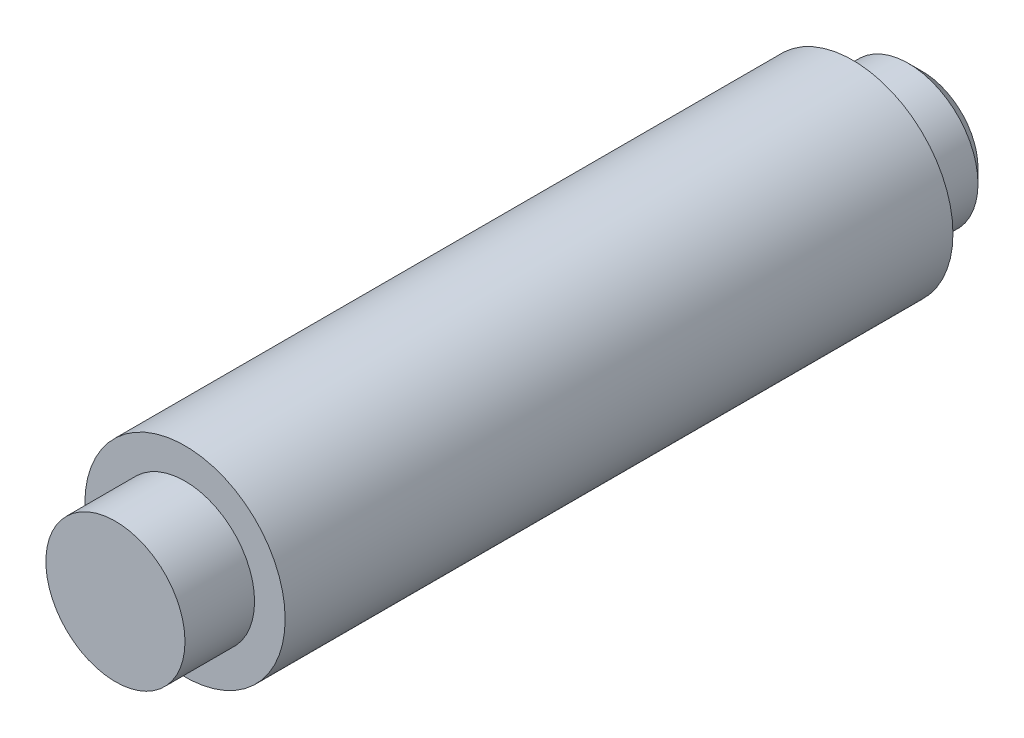
SolidWorks part; units mm, degrees
ref_plane "Front Plane" through (0, 0, 0) normal (0, 0, 1) x (1, 0, 0)
ref_plane "Top Plane" through (0, 0, 0) normal (0, 1, 0) x (1, 0, 0)
ref_plane "Right Plane" through (0, 0, 0) normal (1, 0, 0) x (0, 0, -1)
sketch "Sketch2" plane through (0, 0, 0) normal (0, 0, 1) x (1, 0, 0)
  circle A0 centre (0, 0) radius 1.25
  dimension "D1" = 2.5
sketch "Sketch3" plane through (0, 0, 0) normal (0, 0, 1) x (1, 0, 0)
  line L5 (-3.6, 3.6) -> (3.6, 3.6) construction
  line L6 (-3.6, 3.6) -> (-3.6, -3.6) construction
  line L7 (-3.6, -3.6) -> (3.6, -3.6) construction
  line L8 (3.6, 3.6) -> (3.6, -3.6) construction
  circle A0 centre (0, 0) radius 3.6
  point P4 (0, 3.6)
  point P6 (-3.6, 0)
  dimension "D1" = 7.2
extrude "Boss-Extrude1" add sketch "Sketch3" along normal blind 24
sketch "Sketch4" plane through (0, 0, 0) normal (0, 0, 1) x (1, 0, 0)
  circle A0 centre (0, 0) radius 2.5
  dimension "D1" = 5
extrude "Boss-Extrude2" add sketch "Sketch4" against normal blind 2.5
sketch "Sketch5" plane through (0, 0, 24) normal (0, 0, 1) x (1, 0, 0)
  circle A0 centre (0, 0) radius 2.5
  dimension "D1" = 5
extrude "Boss-Extrude3" add sketch "Sketch5" along normal blind 2.5
chamfer "Chamfer1" distance 0.5 angle 45 1 edges at (2.5, 0, -2.5)
equation "\"length\"=24"
equation "\"D1@Boss-Extrude1\"=\"length\""
